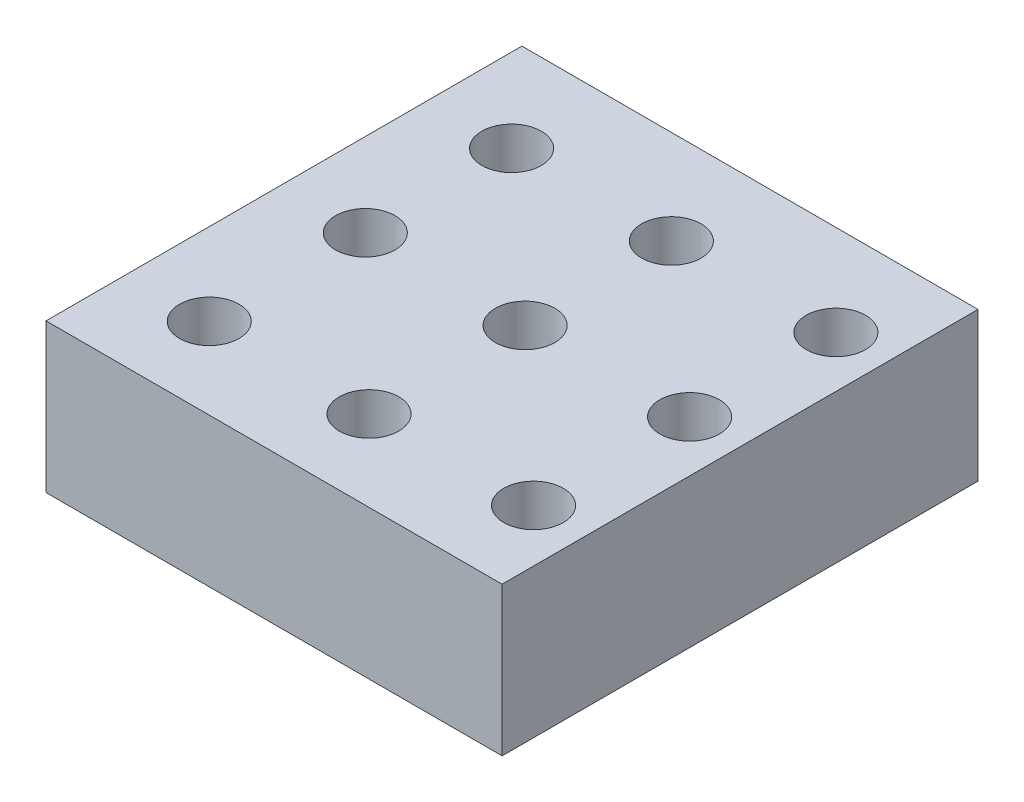
SolidWorks part; units mm, degrees
ref_plane "Front Plane" through (0, 0, 0) normal (0, 0, 1) x (1, 0, 0)
ref_plane "Top Plane" through (0, 0, 0) normal (0, 1, 0) x (1, 0, 0)
ref_plane "Right Plane" through (0, 0, 0) normal (1, 0, 0) x (0, 0, -1)
sketch "Sketch1" plane through (0, 0, 0) normal (0, 1, 0) x (1, 0, 0)
  line L0 (5.6074, 0) -> (5.6074, -32) construction
  line L1 (0, 0) -> (30.6676, 0)
  line L2 (0, 0) -> (0, -32)
  line L3 (0, -32) -> (30.6676, -32)
  line L4 (30.6676, 0) -> (30.6676, -32)
  line L5 (16.3716, -0.0204) -> (16.3716, -32.0204) construction
  line L6 (27.2287, 0.1837) -> (27.2287, -31.8163) construction
  circle A0 centre (5.6074, -6.302) radius 2
  circle A2 centre (5.6074, -16.1364) radius 2
  circle A3 centre (5.5172, -26.5401) radius 2
  circle A4 centre (16.3716, -6.3224) radius 2
  circle A5 centre (16.3716, -16.1568) radius 2
  circle A6 centre (16.2814, -26.5605) radius 2
  circle A7 centre (27.2287, -6.1183) radius 2
  circle A8 centre (27.2287, -15.9527) radius 2
  circle A9 centre (27.1385, -26.3564) radius 2
  dimension "D3" = 4
extrude "Boss-Extrude1" add sketch "Sketch1" along normal blind 10
